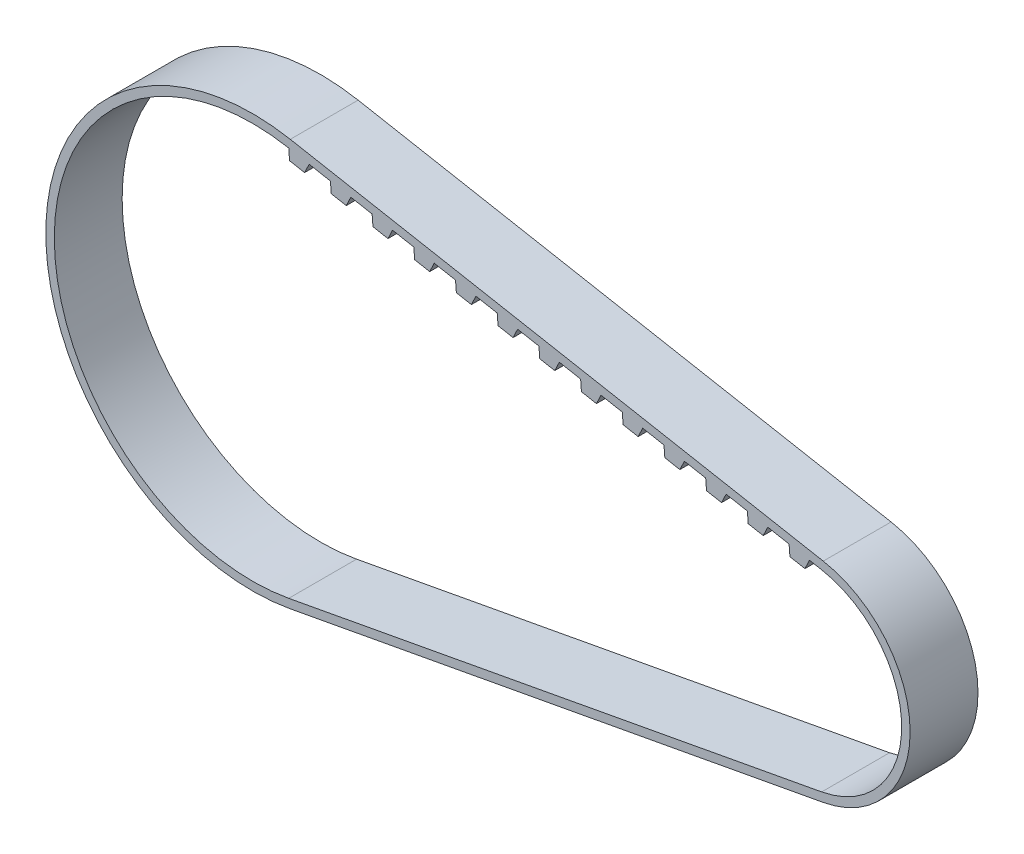
SolidWorks part; units mm, degrees
ref_plane "Front Plane" through (0, 0, 0) normal (0, 0, 1) x (1, 0, 0)
ref_plane "Top Plane" through (0, 0, 0) normal (0, 1, 0) x (1, 0, 0)
ref_plane "Right Plane" through (0, 0, 0) normal (1, 0, 0) x (0, 0, -1)
sketch "Sketch1" plane through (0, 0, 0) normal (0, 0, 1) x (1, 0, 0)
  line L0 (67.102, 11.3368) -> (4.2624, 22.9882)
  line L1 (4.2624, -22.9882) -> (67.102, -11.3368)
  line L2 (0, 0) -> (65, 0) construction
  arc A0 (4.2624, 22.9882) -> (4.2624, -22.9882) centre (0, 0) ccw
  arc A1 (67.102, -11.3368) -> (67.102, 11.3368) centre (65, 0) ccw
  dimension "D2" = 46.76
  dimension "D3" = 23.06
  dimension "D1" = 65
sketch "Sketch2" plane through (0, 0, 0) normal (0, 0, 1) x (1, 0, 0)
  line L0 (4.2624, -22.9882) -> (67.102, -11.3368) construction
  line L1 (67.102, 11.3368) -> (4.2624, 22.9882) construction
  line L2 (4.2624, -22.9882) -> (67.102, -11.3368)
  line L3 (67.102, 11.3368) -> (4.2624, 22.9882)
  line L4 (67.2843, 12.32) -> (4.4447, 23.9714)
  line L5 (4.4447, -23.9714) -> (67.2843, -12.32)
  arc A0 (67.102, -11.3368) -> (67.102, 11.3368) centre (65, 0) ccw construction
  arc A1 (4.2624, 22.9882) -> (4.2624, -22.9882) centre (0, 0) ccw construction
  arc A2 (67.102, -11.3368) -> (67.102, 11.3368) centre (65, 0) ccw
  arc A3 (4.2624, 22.9882) -> (4.2624, -22.9882) centre (0, 0) ccw
  arc A4 (4.4447, 23.9714) -> (4.4447, -23.9714) centre (0, 0) ccw
  arc A5 (67.2843, -12.32) -> (67.2843, 12.32) centre (65, 0) ccw
  dimension "D1" = 1
extrude "Boss-Extrude1" add sketch "Sketch2" along normal blind 8
sketch "Sketch4" plane through (0, 0, 0) normal (0, 0, 1) x (1, 0, 0)
  line L0 (4.2624, 22.9882) -> (4.0422, 21.801) construction
  line L1 (4.0422, 21.801) -> (8.5739, 20.9608) construction
  line L2 (8.5739, 20.9608) -> (8.794, 22.148) construction
  line L3 (67.102, 11.3368) -> (4.2624, 22.9882) construction
  line L4 (8.794, 22.148) -> (4.2624, 22.9882) construction
  line L5 (4.2624, 22.9882) -> (4.3603, 21.742)
  line L6 (4.3603, 21.742) -> (6.1302, 21.4139)
  line L7 (6.1302, 21.4139) -> (6.6684, 22.5421)
  line L10 (6.6684, 22.5421) -> (4.2624, 22.9882)
  dimension "D1" = 1.25
  dimension "D3" = 15
  dimension "D4" = 15
  dimension "D8" = 1.8
extrude "Boss-Extrude2" add sketch "Sketch4" along normal blind 8
pattern_curve "CrvPattern1" of "Boss-Extrude2" parameters "D1"=48, "D3"=5, "D2"=1, "D4"=50
